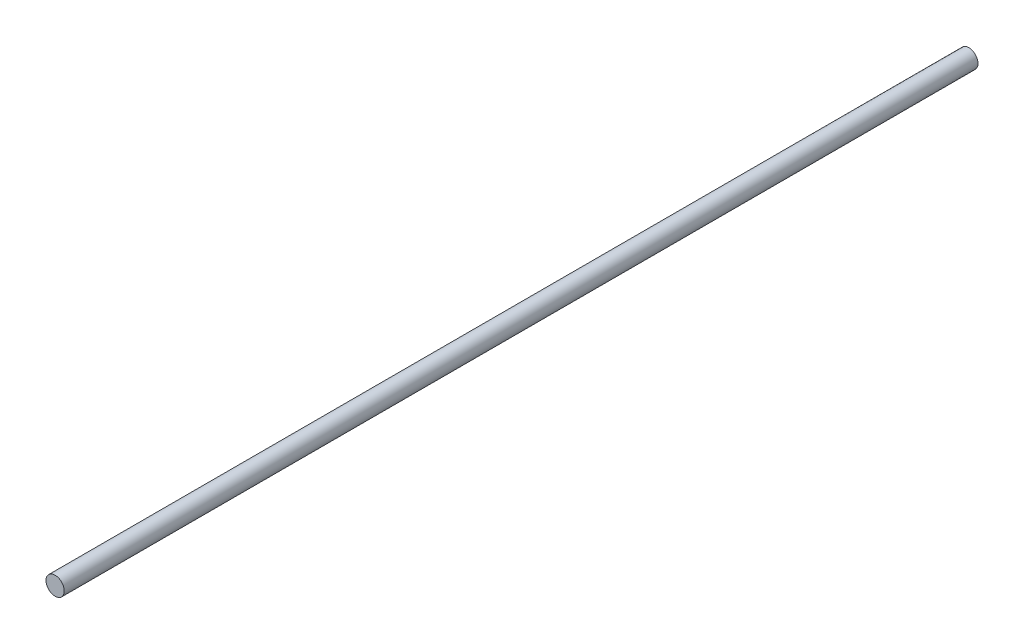
SolidWorks part; units mm, degrees
ref_plane "Alzado" through (0, 0, 0) normal (0, 0, 1) x (1, 0, 0)
ref_plane "Planta" through (0, 0, 0) normal (0, 1, 0) x (1, 0, 0)
ref_plane "Vista lateral" through (0, 0, 0) normal (1, 0, 0) x (0, 0, -1)
sketch "Croquis1" plane through (0, 0, 0) normal (0, 0, 1) x (1, 0, 0)
  circle A0 centre (0, 0) radius 0.5
  dimension "D1" = 1
extrude "Saliente-Extruir1" add sketch "Croquis1" along normal blind 50
